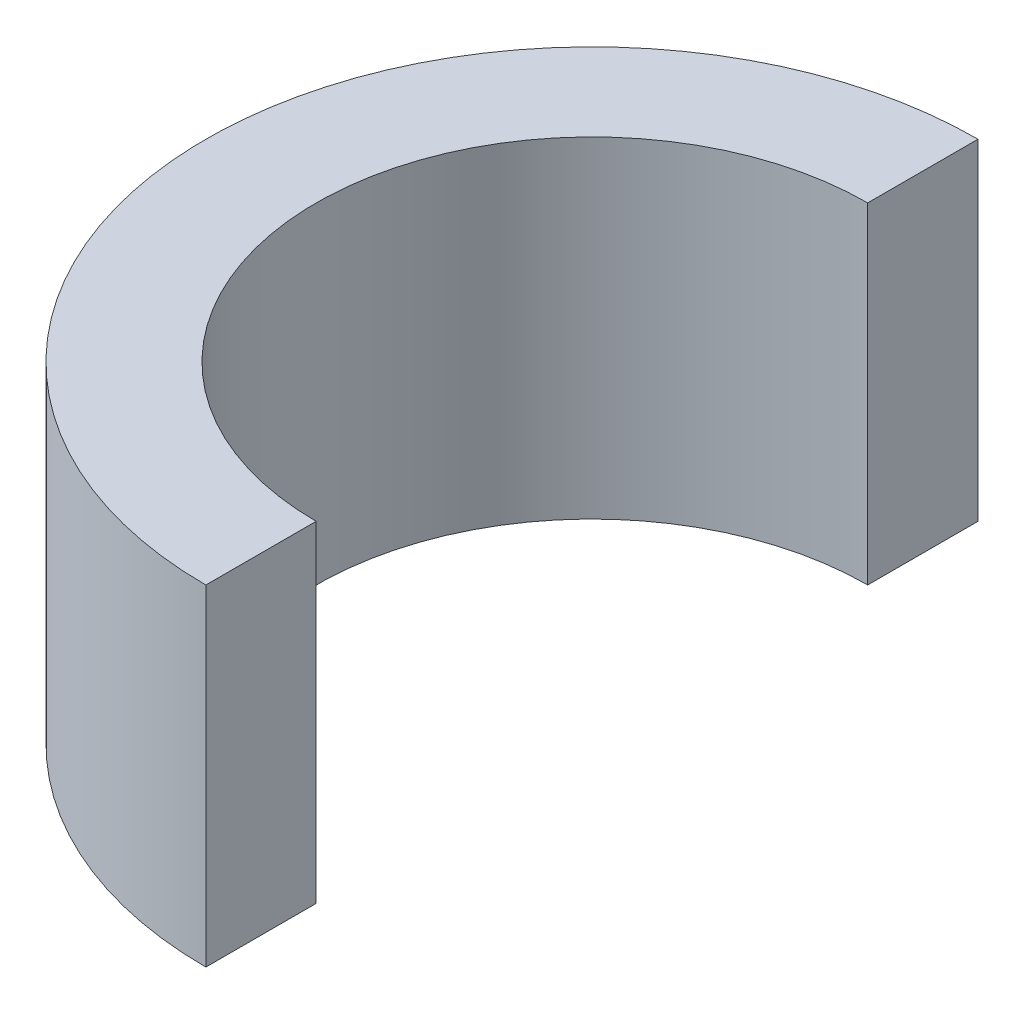
SolidWorks part; units mm, degrees
ref_plane "前视基准面" through (0, 0, 0) normal (0, 0, 1) x (1, 0, 0)
ref_plane "上视基准面" through (0, 0, 0) normal (0, 1, 0) x (1, 0, 0)
ref_plane "右视基准面" through (0, 0, 0) normal (1, 0, 0) x (0, 0, -1)
other "Configuration Table"
sketch "草图1" plane through (0, 0, 0) normal (0, 1, 0) x (1, 0, 0)
  line L1 (0, 5) -> (0, 7)
  line L2 (0, 7) -> (0, 5)
  line L3 (0, -5) -> (0, -7)
  arc A0 (0, 5) -> (0, -5) centre (0, 0) ccw
  arc A1 (0, 7) -> (0, -7) centre (0, 0) ccw
  dimension "D1" = 5
  dimension "D2" = 2
extrude "凸台-拉伸1" add sketch "草图1" along normal blind 6 contours L1 A1 L3 A0
